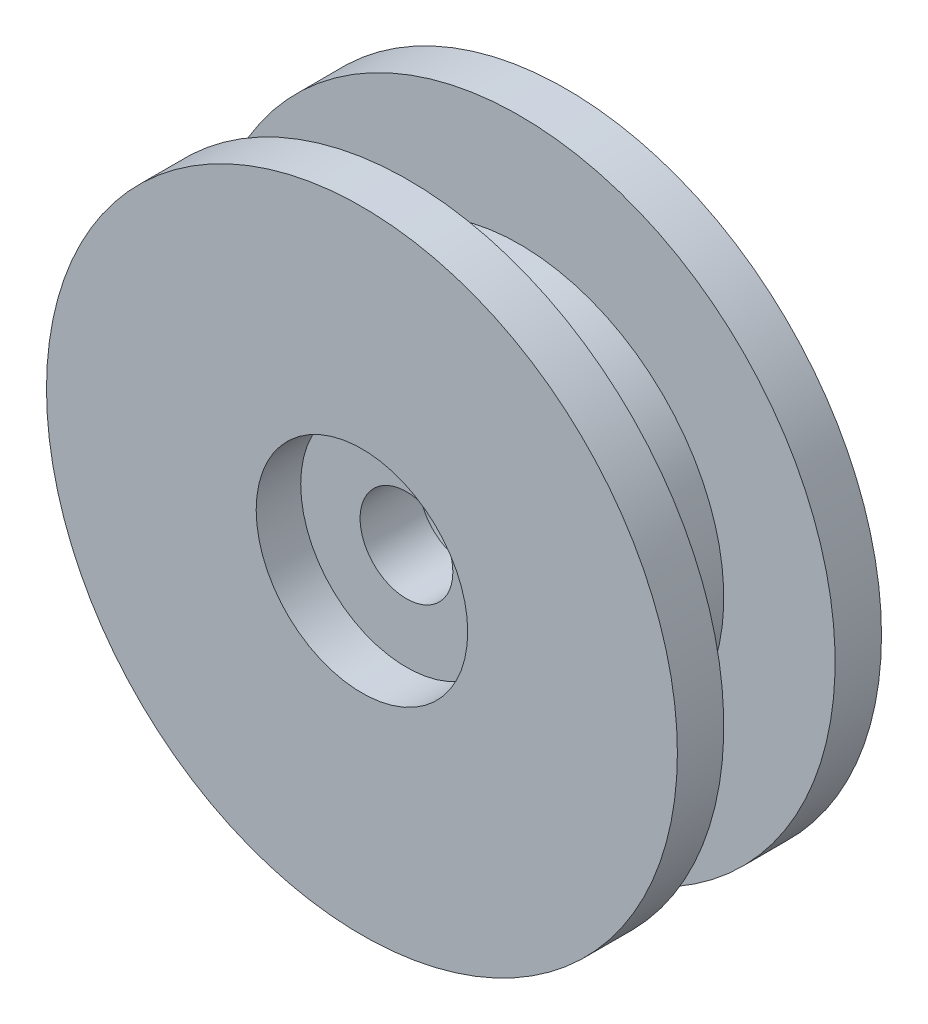
SolidWorks part; units mm, degrees
ref_plane "Alzado" through (0, 0, 0) normal (0, 0, 1) x (1, 0, 0)
ref_plane "Planta" through (0, 0, 0) normal (0, 1, 0) x (1, 0, 0)
ref_plane "Vista lateral" through (0, 0, 0) normal (1, 0, 0) x (0, 0, -1)
sketch "Croquis1" plane through (0, 0, 0) normal (0, 0, 1) x (1, 0, 0)
  circle A0 centre (0, 0) radius 8.5
  dimension "D1" = 17
extrude "Saliente-Extruir1" add sketch "Croquis1" along normal blind 5.5
sketch "Croquis2" plane through (0, 0, 0) normal (1, 0, 0) x (0, 0, -1)
  line L0 (0, 8.5) -> (-5.5, 8.5) construction
  line L1 (0, 8.5) -> (-5.5, 8.5) construction
  line L2 (-5.5, 8.5) -> (-4.25, 8.5)
  line L3 (-4.25, 8.5) -> (-4.25, 5.5)
  line L4 (-4.25, 5.5) -> (-1.25, 5.5)
  line L5 (-1.25, 5.5) -> (-1.25, 8.5)
  line L6 (-1.25, 8.5) -> (0, 8.5)
  line L7 (-2.75, 8.5) -> (-2.75, 5.5) construction
  line L8 (0, 0) -> (-5.5, 0) construction
  line L9 (-5.5, 8.5) -> (-5.5, -8.5) construction
  line L10 (-5.5, 8.5) -> (-5.5, 8.9522)
  line L11 (-5.5, 8.9522) -> (0, 8.9522)
  line L12 (0, 8.9522) -> (0, 8.5)
  point P8 (-2.75, 5.5)
  dimension "D1" = 3
  dimension "D2" = 3
revolve "Cortar-Revolución1" cut sketch "Croquis2" angle 360 about L8
sketch "Croquis3" plane through (0, 0, 5.5) normal (0, 0, 1) x (1, 0, 0)
  circle A0 centre (0, 0) radius 2.85
  dimension "D1" = 5.7
extrude "Cortar-Extruir1" cut sketch "Croquis3" against normal blind 1.2
sketch "Croquis4" plane through (0, 0, 5.5) normal (0, 0, 1) x (1, 0, 0)
  circle A0 centre (0, 0) radius 1.25
  dimension "D1" = 2.5
extrude "Cortar-Extruir2" cut sketch "Croquis4" against normal through all
sketch "Croquis5" plane through (0, 0, 0) normal (0, 0, -1) x (-1, 0, 0)
  circle A0 centre (0, 0) radius 2.32
  dimension "D1" = 4.64
extrude "Cortar-Extruir3" cut sketch "Croquis5" against normal blind 2.7
